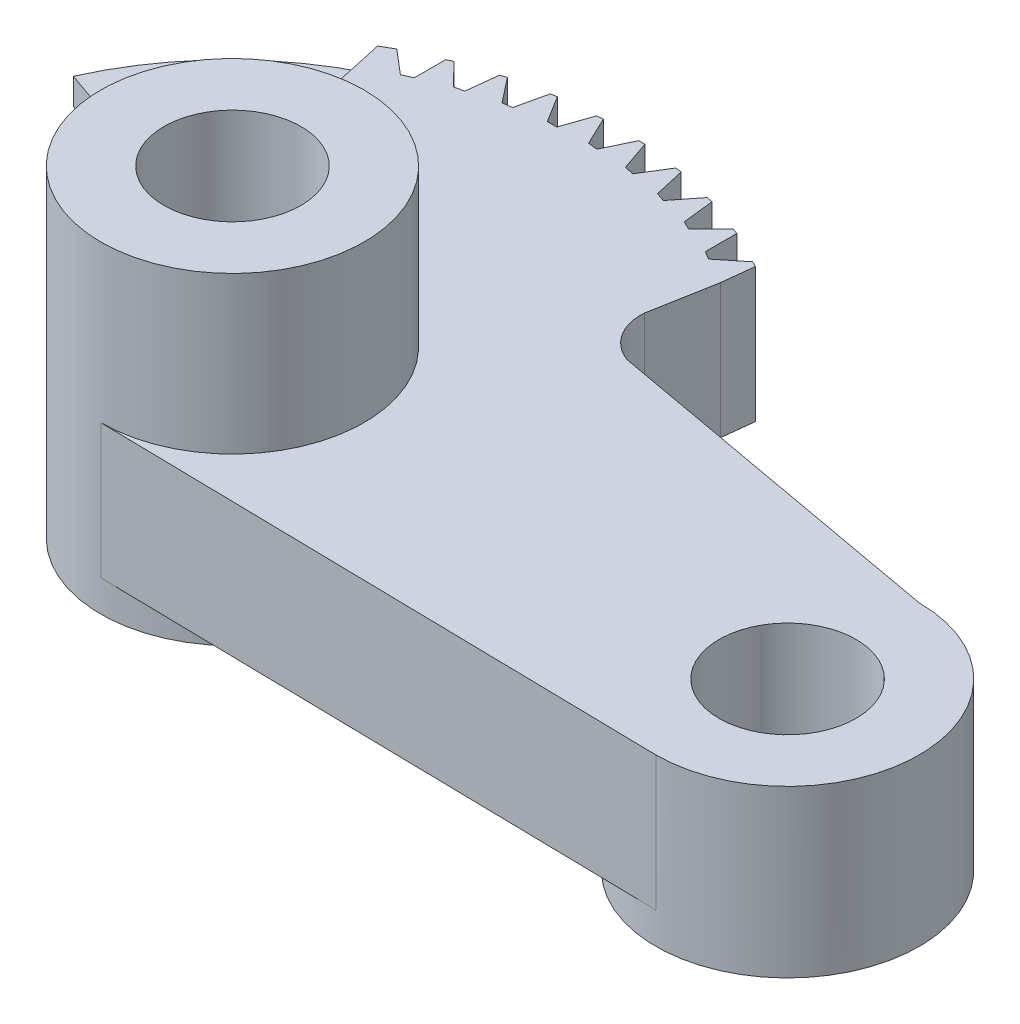
SolidWorks part; units mm, degrees
ref_plane "Спереди" through (0, 0, 0) normal (0, 0, 1) x (1, 0, 0)
ref_plane "Сверху" through (0, 0, 0) normal (0, 1, 0) x (1, 0, 0)
ref_plane "Справа" through (0, 0, 0) normal (1, 0, 0) x (0, 0, -1)
sketch "Эскиз1" plane through (0, 0, 0) normal (0, 1, 0) x (1, 0, 0)
  line L0 (-8.1147, 3.9642) -> (30.3411, -3.1046) construction
  line L1 (-7.0258, 12.1759) -> (-7.131, 12.6394)
  line L2 (0, -5) -> (21.4669, -5.3883)
  line L3 (21.4669, 4.6117) -> (7.9243, 7.0621)
  line L4 (6.718, 8.9283) -> (7.1612, 11.3779)
  line L5 (-2.8983, 13.1359) -> (-3.6342, 14.0716)
  line L6 (-4.339, 12.734) -> (-5.1742, 13.5822)
  line L7 (-3.9893, 12.8157) -> (-3.8571, 13.9987)
  line L9 (-7.131, 12.6394) -> (-6.6667, 12.9059)
  line L10 (-6.6667, 12.9059) -> (-5.7516, 12.1288)
  line L11 (-5.7516, 12.1288) -> (-5.3876, 12.2946)
  line L12 (-3.8571, 13.9987) -> (-3.6342, 14.0716)
  line L13 (-1.422, 13.3754) -> (-2.0494, 14.387)
  line L14 (-2.5417, 13.1782) -> (-2.279, 14.3393)
  line L39 (-2.279, 14.3393) -> (-2.0494, 14.387)
  line L40 (0.0718, 13.4494) -> (-0.4394, 14.5244)
  line L41 (-1.0629, 13.3778) -> (-0.6729, 14.5025)
  line L42 (-0.6729, 14.5025) -> (-0.4394, 14.5244)
  line L43 (1.5646, 13.3571) -> (1.1759, 14.4822)
  line L44 (0.4289, 13.412) -> (0.9414, 14.4864)
  line L45 (0.9414, 14.4864) -> (1.1759, 14.4822)
  line L46 (3.0379, 13.0996) -> (2.7766, 14.261)
  line L47 (1.9154, 13.2803) -> (2.544, 14.2911)
  line L48 (2.544, 14.2911) -> (2.7766, 14.261)
  line L49 (4.4735, 12.6801) -> (4.3427, 13.8633)
  line L50 (3.378, 12.9843) -> (4.1149, 13.9191)
  line L51 (4.1149, 13.9191) -> (4.3427, 13.8633)
  line L52 (5.8536, 12.1038) -> (5.8551, 13.2942)
  line L53 (4.7987, 12.5278) -> (5.6349, 13.375)
  line L54 (5.6349, 13.375) -> (5.8551, 13.2942)
  line L55 (7.1612, 11.3779) -> (7.2948, 12.5607)
  line L56 (6.1599, 11.9163) -> (7.085, 12.6654)
  line L57 (7.085, 12.6654) -> (7.2948, 12.5607)
  line L58 (-4.339, 12.734) -> (-3.9893, 12.8157)
  line L59 (-2.8983, 13.1359) -> (-2.5417, 13.1782)
  line L60 (-1.422, 13.3754) -> (-1.0629, 13.3778)
  line L61 (0.0718, 13.4494) -> (0.4289, 13.412)
  line L62 (1.5646, 13.3571) -> (1.9154, 13.2803)
  line L63 (3.0379, 13.0996) -> (3.378, 12.9843)
  line L64 (4.4735, 12.6801) -> (4.7987, 12.5278)
  line L65 (5.8536, 12.1038) -> (6.1599, 11.9163)
  line L66 (-5.3876, 13.485) -> (-5.3876, 12.2946)
  line L67 (-5.3876, 13.485) -> (-5.1742, 13.5822)
  line L68 (-5.2411, 3.925) -> (-4.7377, 1.5981)
  line L69 (-12.5111, 6.4702) -> (-5.2411, 3.925)
  arc A0 (-4.7377, 1.5981) -> (0, -5) centre (0, 0) ccw
  arc A1 (21.2861, -5.385) -> (21.4669, 4.6117) centre (21.4669, -0.3883) ccw
  arc A2 (7.9243, 7.0621) -> (6.718, 8.9283) centre (8.5382, 8.7819) cw
  arc A3 (-5.4397, 3.9952) -> (-5.4396, 3.9945) centre (1.2447, 4.6512) ccw
  arc A4 (-12.5111, 6.4702) -> (-7.0258, 12.1759) centre (-1.8095, 1.6715) cw
  circle A5 centre (21.4669, -0.3883) radius 2.5
  circle A6 centre (0, 0) radius 2.5
  point P89 (-0.0104, 0.0012)
  dimension "D2" = 1.8261
  dimension "D3" = 9
  dimension "D1" = 39.1
extrude "Бобышка-Вытянуть1" add sketch "Эскиз1" along normal blind 5.1
sketch "Эскиз2" plane through (0, 5.1, 0) normal (0, 1, 0) x (1, 0, 0)
  circle A0 centre (0, 0) radius 5
  circle A1 centre (0, 0) radius 2.5
extrude "Бобышка-Вытянуть2" add sketch "Эскиз2" along normal blind 5.94
sketch "Эскиз4" plane through (0, 0, 0) normal (0, -1, 0) x (1, 0, 0)
  line L0 (-5.2411, -3.925) -> (-7.0258, -12.1759)
  line L1 (-12.5111, -6.4702) -> (-5.2411, -3.925)
  arc A0 (-7.0258, -12.1759) -> (-12.5111, -6.4702) centre (-1.8095, -1.6715) cw
  dimension "D1" = 11.7282
extrude "Вырез-Вытянуть1" cut sketch "Эскиз4" against normal blind 3.5
sketch "Эскиз5" plane through (0, 5.1, 0) normal (0, 1, 0) x (1, 0, 0)
  line L0 (-5.2411, 3.925) -> (-7.0258, 12.1759)
  line L1 (-12.5111, 6.4702) -> (-5.2411, 3.925)
  arc A0 (-7.0258, 12.1759) -> (-12.5111, 6.4702) centre (-1.8095, 1.6715) ccw
  dimension "D1" = 11.7282
extrude "Вырез-Вытянуть3" cut sketch "Эскиз5" against normal blind 0.6
sketch "Эскиз6" plane through (0, 0, 0) normal (0, -1, 0) x (1, 0, 0)
  circle A0 centre (0, 0) radius 5
  circle A1 centre (0, 0) radius 2.5
  circle A2 centre (21.4669, 0.3883) radius 2.5
  circle A3 centre (21.4669, 0.3883) radius 5
extrude "Бобышка-Вытянуть4" add sketch "Эскиз6" along normal blind 1.2
sketch "Эскиз7" plane through (0, 11.04, 0) normal (0, 1, 0) x (1, 0, 0)
  circle A0 centre (0, 0) radius 2.6
extrude "Вырез-Вытянуть4" cut sketch "Эскиз7" against normal through all
sketch "Эскиз8" plane through (0, 5.1, 0) normal (0, 1, 0) x (1, 0, 0)
  circle A0 centre (21.4669, -0.3883) radius 2.6
extrude "Вырез-Вытянуть5" cut sketch "Эскиз8" against normal through all
